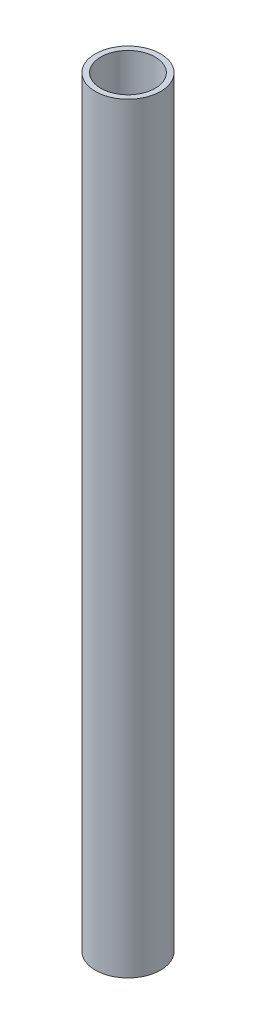
SolidWorks part; units mm, degrees
ref_plane "Спереди" through (0, 0, 0) normal (0, 0, 1) x (1, 0, 0)
ref_plane "Сверху" through (0, 0, 0) normal (0, 1, 0) x (1, 0, 0)
ref_plane "Справа" through (0, 0, 0) normal (1, 0, 0) x (0, 0, -1)
sketch "Эскиз1" plane through (0, 0, 0) normal (0, 1, 0) x (1, 0, 0)
  circle A0 centre (0, 0) radius 12.5
  circle A1 centre (0, 0) radius 15
extrude "Вытянуть1" add sketch "Эскиз1" along normal blind 350
